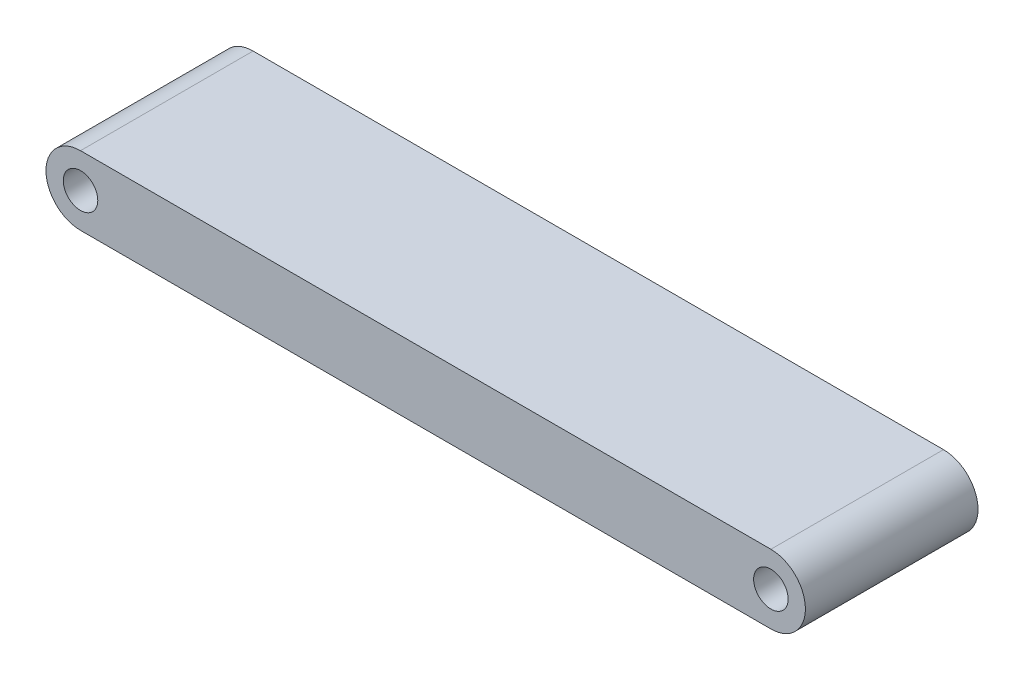
SolidWorks part; units mm, degrees
material "ﾊﾞﾙｻ"
ref_plane "正面" through (0, 0, 0) normal (0, 0, 1) x (1, 0, 0)
ref_plane "平面" through (0, 0, 0) normal (0, 1, 0) x (1, 0, 0)
ref_plane "右側面" through (0, 0, 0) normal (1, 0, 0) x (0, 0, -1)
sketch "ｽｹｯﾁ1" plane through (0, 0, 0) normal (0, 0, 1) x (1, 0, 0)
  line L1 (-2000, -200) -> (2000, -200)
  line L2 (-2000, -200) -> (-2000, 200)
  line L3 (-2000, 200) -> (2000, 200)
  line L4 (2000, -200) -> (2000, 200)
  line L5 (-2000, -200) -> (2000, 200) construction
  line L6 (-2000, 200) -> (2000, -200) construction
  circle A0 centre (-2000, 0) radius 200
  circle A1 centre (-2000, 0) radius 100
  circle A2 centre (2000, 0) radius 200
  circle A3 centre (2000, 0) radius 100
  point P0 (0, 0)
extrude "ﾎﾞｽ - 押し出し1" add sketch "ｽｹｯﾁ1" along normal blind 1000 contours A1 L2 A0 | A1 L2 A0 | A2 L3 A0 L1 | A3 L4 A2 | A3 L4 A2
